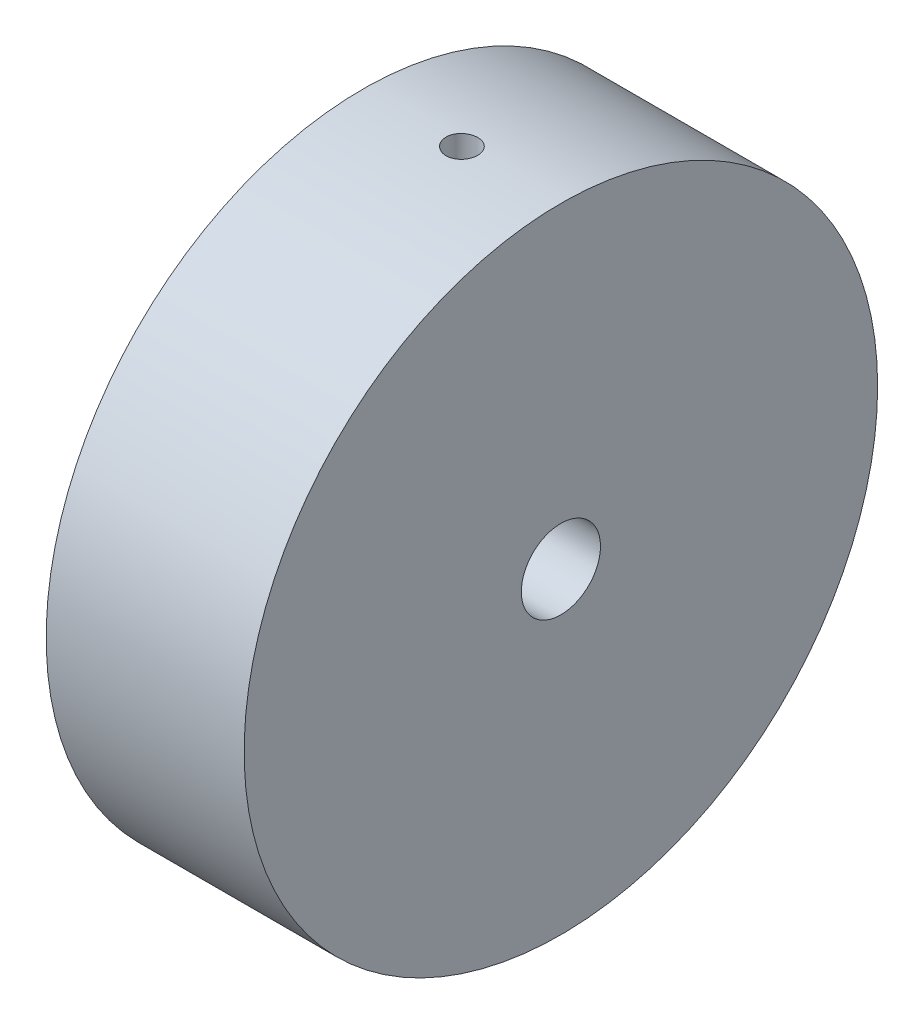
SolidWorks part; units mm, degrees
material "3.1645 (EN AW-2007)"
ref_plane "Plano frontal" through (0, 0, 0) normal (0, 0, 1) x (1, 0, 0)
ref_plane "Plano superior" through (0, 0, 0) normal (0, 1, 0) x (1, 0, 0)
ref_plane "Plano direito" through (0, 0, 0) normal (1, 0, 0) x (0, 0, -1)
sketch "Esboço3" plane through (0, 0, 0) normal (0, 0, 1) x (1, 0, 0)
  line L0 (0, 0) -> (-50.7324, 0) construction
  line L1 (0, 16) -> (0, 2)
  line L2 (-2, 14) -> (-2, 5)
  line L3 (-10, 5) -> (-10, 0)
  line L4 (-2, 5) -> (-10, 5)
  line L5 (-10, 0) -> (-8, 0)
  line L6 (-8, 2) -> (0, 2)
  line L7 (-2, 14) -> (-10, 14)
  line L8 (-10, 14) -> (-10, 16)
  line L9 (-10, 16) -> (0, 16)
  line L10 (-8, 0) -> (-8, 2)
  dimension "D1" = 2
  dimension "D2" = 16
  dimension "D3" = 2
  dimension "D4" = 10
  dimension "D5" = 5
  dimension "D6" = 2
  dimension "D7" = 10
  dimension "D8" = 2
revolve "Revolução1" add sketch "Esboço3" angle 360 about L0
ref_plane "Plano1" through (0, 5, 0) normal (0, 1, 0) x (1, 0, 0)
sketch "Esboço6" plane through (0, 5, 0) normal (0, 1, 0) x (1, 0, 0)
  line L0 (-10, 16) -> (-10, -16) construction
  circle A0 centre (-5, 0) radius 0.8
  dimension "D1" = 1.6
  dimension "D2" = 5
extrude "Corte-extrusão1" cut sketch "Esboço6" against normal mid plane 70
equation "\"D4@Esboço3\"=\"D7@Esboço3\""
